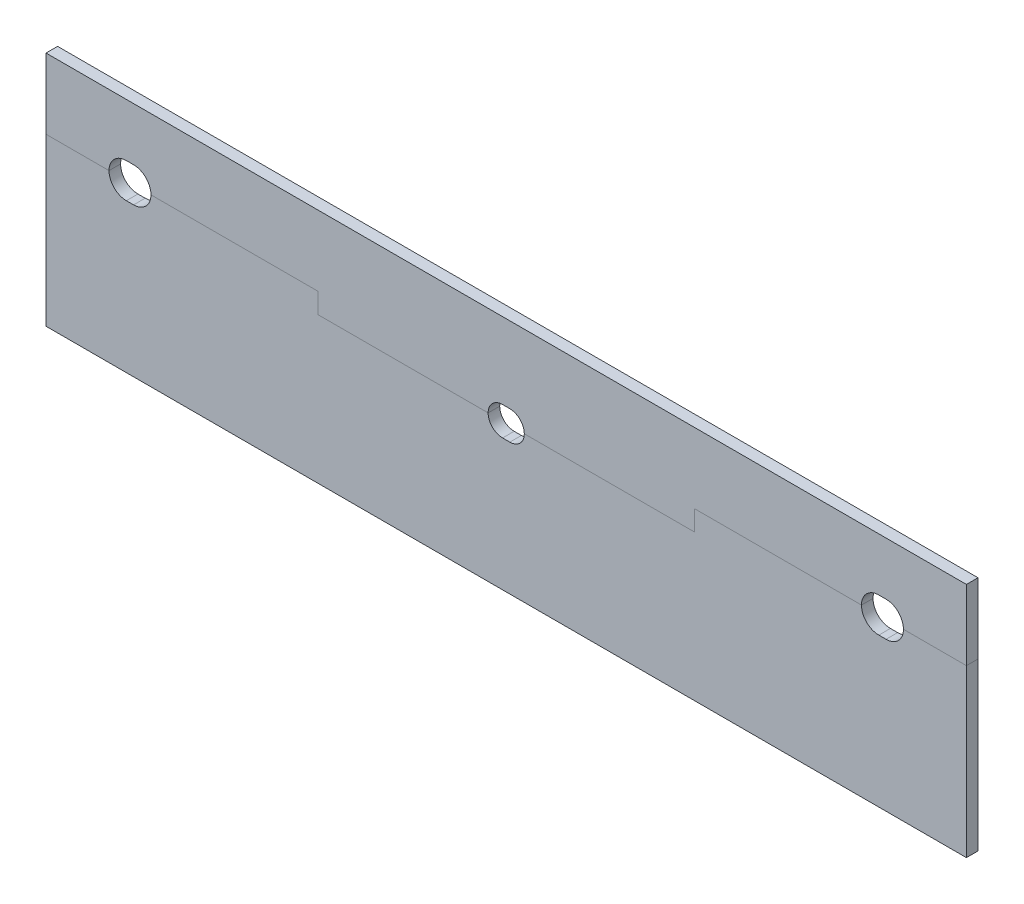
SolidWorks part; units mm, degrees
ref_plane "Front Plane" through (0, 0, 0) normal (1, 0, 0) x (0, 1, 0)
ref_plane "Top Plane" through (0, 0, 0) normal (0, 0, 1) x (0, 1, 0)
ref_plane "Right Plane" through (0, 0, 0) normal (0, 1, 0) x (-1, 0, 0)
sketch "Sketch1" plane through (0, 0, 0) normal (0, 0, 1) x (0, 1, 0)
  line L0 (0, 130) -> (0, -130) construction
  line L1 (0, 128.75) -> (0, 131.25) construction
  line L2 (-6, 128.75) -> (-6, 131.25)
  line L3 (6, 128.75) -> (6, 131.25)
  line L4 (0, -131.25) -> (0, -128.75) construction
  line L5 (-6, -131.25) -> (-6, -128.75)
  line L6 (6, -131.25) -> (6, -128.75)
  line L7 (-16.5795, 0) -> (0, 0) construction
  line L10 (-57.4635, -159.0193) -> (24.3044, -159.0193)
  line L11 (-57.4635, -159.0193) -> (-57.4635, 159.0193)
  line L12 (-57.4635, 159.0193) -> (24.3044, 159.0193)
  line L13 (24.3044, -159.0193) -> (24.3044, 159.0193)
  line L14 (-57.4635, -159.0193) -> (24.3044, 159.0193) construction
  line L15 (-57.4635, 159.0193) -> (24.3044, -159.0193) construction
  line L16 (-7, 0) -> (0, 0) construction
  line L17 (-7, 1.25) -> (-7, -1.25) construction
  line L18 (-2, 1.25) -> (-2, -1.25)
  line L19 (-12, 1.25) -> (-12, -1.25)
  arc A0 (-6, 128.75) -> (6, 128.75) centre (0, 128.75) ccw
  arc A1 (6, 131.25) -> (-6, 131.25) centre (0, 131.25) ccw
  arc A2 (-6, -131.25) -> (6, -131.25) centre (0, -131.25) ccw
  arc A3 (6, -128.75) -> (-6, -128.75) centre (0, -128.75) ccw
  arc A7 (-2, 1.25) -> (-12, 1.25) centre (-7, 1.25) ccw
  arc A8 (-12, -1.25) -> (-2, -1.25) centre (-7, -1.25) ccw
  point P7 (0, 130)
  point P13 (0, -130)
  point P20 (-16.5795, 0)
  point P31 (-7, 0)
  dimension "D3" = 6
  dimension "D5" = 5
  dimension "D1" = 260
  dimension "D2" = 2.5
  dimension "D4" = 7
extrude "Boss-Extrude1" add sketch "Sketch1" along normal blind 4
sketch "Sketch2" plane through (0, 0, 4) normal (0, 0, 1) x (1, 0, 0)
  line L0 (-159.0193, 0) -> (-65, 0)
  line L1 (-159.0193, 24.3044) -> (-159.0193, -57.4635) construction
  line L2 (-65, 0) -> (-65, -7)
  line L3 (-65, -7) -> (65, -7)
  line L4 (65, -7) -> (65, 0)
  line L5 (65, 0) -> (159.0193, 0)
  line L6 (159.0193, -57.4635) -> (159.0193, 24.3044) construction
  line L7 (128.75, 6) -> (128.75, -6)
  line L8 (0, 0) -> (0, -7)
  arc A1 (1.25, -12) -> (1.25, -2) centre (1.25, -7) ccw construction
  point P15 (6.25, -7)
  point P21 (-58.2434, 0)
  dimension "D1" = 130
split "Split1" trim tools "Sketch2" bodies to split 101 resulting bodies 102 103
